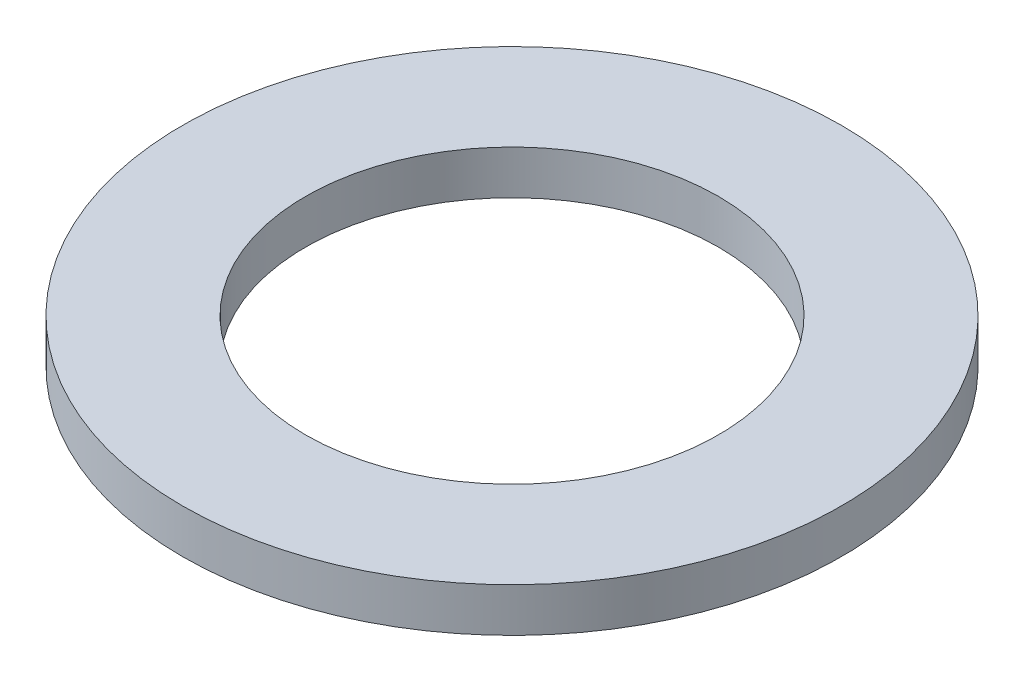
SolidWorks part; units mm, degrees
material "Caoutchouc silicone"
ref_plane "Plan de face" through (0, 0, 0) normal (0, 0, 1) x (1, 0, 0)
ref_plane "Plan de dessus" through (0, 0, 0) normal (0, 1, 0) x (1, 0, 0)
ref_plane "Plan de droite" through (0, 0, 0) normal (1, 0, 0) x (0, 0, -1)
sketch "Esquisse2" plane through (0, 0, 0) normal (0, 1, 0) x (1, 0, 0)
  circle A0 centre (0, 0) radius 4.7
  circle A1 centre (0, 0) radius 7.5
  dimension "D1" = 9.4
  dimension "D2" = 15
extrude "Boss.-Extru.1" add sketch "Esquisse2" along normal blind 1
equation "\"ç\"=0.105877"
